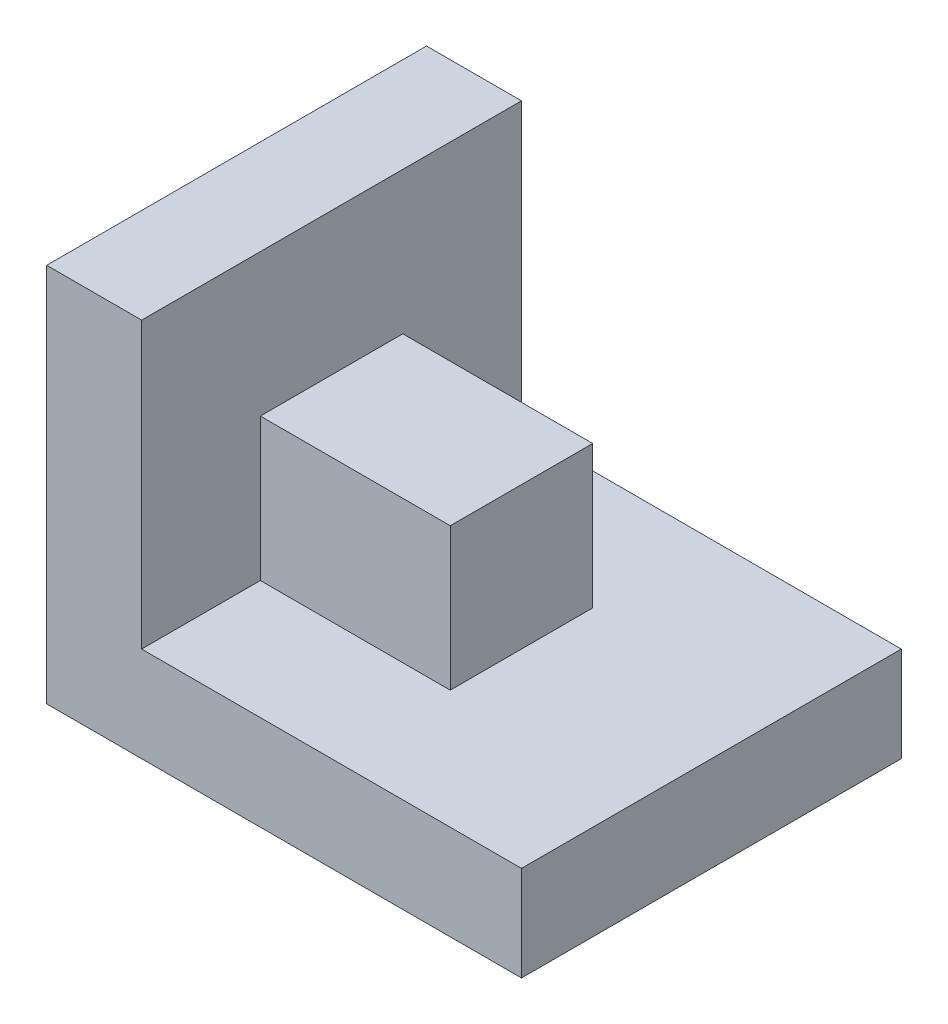
SolidWorks part; units mm, degrees
ref_plane "Front Plane" through (0, 0, 0) normal (0, 0, 1) x (1, 0, 0)
ref_plane "Top Plane" through (0, 0, 0) normal (0, 1, 0) x (1, 0, 0)
ref_plane "Right Plane" through (0, 0, 0) normal (1, 0, 0) x (0, 0, -1)
sketch "Sketch1" plane through (0, 0, 0) normal (0, 0, 1) x (1, 0, 0)
  line L0 (-23.4375, 10) -> (-33.4375, 10)
  line L1 (-33.4375, 10) -> (-33.4375, -30)
  line L2 (-33.4375, -30) -> (16.5625, -30)
  line L3 (16.5625, -30) -> (16.5625, -20)
  line L4 (16.5625, -20) -> (-23.4375, -20)
  line L5 (-23.4375, -20) -> (-23.4375, 10)
  dimension "D1" = 10
  dimension "D2" = 40
  dimension "D3" = 30
  dimension "D4" = 50
extrude "Boss-Extrude1" add sketch "Sketch1" along normal blind 40
sketch "Sketch2" plane through (-23.4375, 0, 0) normal (1, 0, 0) x (0, 0, -1)
  line L10 (-40, -20) -> (0, -20) construction
  line L11 (-12.5, -5) -> (-27.5, -5)
  line L12 (-12.5, -5) -> (-12.5, -20)
  line L13 (-12.5, -20) -> (-27.5, -20)
  line L14 (-27.5, -5) -> (-27.5, -20)
  line L15 (-12.5, -5) -> (-27.5, -20) construction
  line L16 (-12.5, -20) -> (-27.5, -5) construction
  point P0 (-20, -12.5)
  dimension "D1" = 15
  dimension "D2" = 15
  dimension "D3" = 12.5
extrude "Boss-Extrude2" add sketch "Sketch2" along normal blind 20
